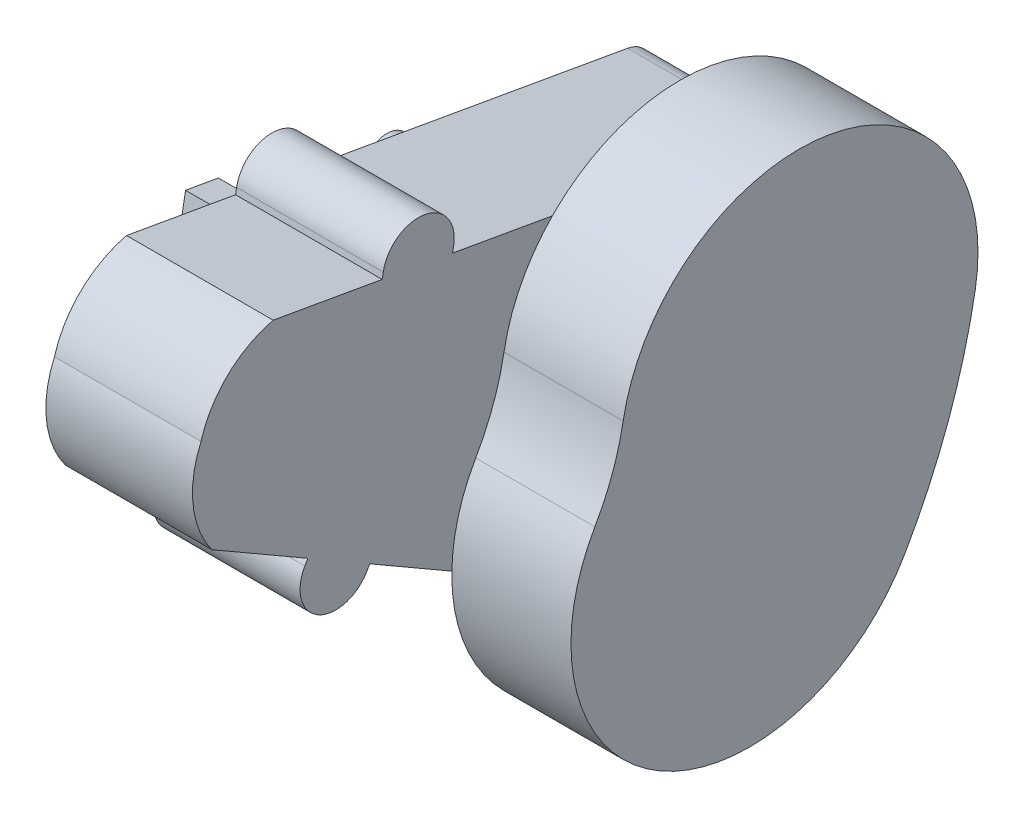
SolidWorks part; units mm, degrees
ref_plane "Front Plane" through (0, 0, 0) normal (0, 0, 1) x (1, 0, 0)
ref_plane "Top Plane" through (0, 0, 0) normal (0, 1, 0) x (1, 0, 0)
ref_plane "Right Plane" through (0, 0, 0) normal (1, 0, 0) x (0, 0, -1)
sketch "Sketch1" plane through (0, 0, 0) normal (1, 0, 0) x (0, 0, -1)
  line L0 (3.1052, 15.25) -> (16, 12.9763) construction
  line L1 (3.1052, 15.25) -> (16, 12.9763) construction
  line L2 (-0.2321, -17.5002) -> (-13.4374, -9.8761) construction
  line L3 (-0.2321, -17.5002) -> (-13.4374, -9.8761) construction
sketch "Sketch2"
sketch_block_instance "Block2-1"
sketch_block "Block2"
sketch "Sketch5" plane through (21.6, 0, 0) normal (1, 0, 0) x (0, 0, -1)
  line L1 (-0.2321, -17.5002) -> (-13.4374, -9.8761) construction
  line L2 (3.1052, 15.25) -> (16, 12.9763) construction
  line B0 (7.625, 13.2069) -> (-7.625, -13.2069)
  line B1 (8.4666, -22.4974) -> (7.9666, -23.3634)
  line B2 (18.3589, -29.3634) -> (18.8589, -28.4974)
  line B3 (18.8589, -28.4974) -> (66.3162, -55.8969)
  line B4 (73.1464, -54.0668) -> (83.3964, -36.3132)
  line B5 (81.5662, -29.4831) -> (34.1089, -2.0836)
  line B6 (34.1089, -2.0836) -> (34.6089, -1.2176)
  line B7 (24.2166, 4.7824) -> (23.7166, 3.9164)
  line B8 (23.7166, 3.9164) -> (7.625, 13.2069)
  line B9 (-7.625, -13.2069) -> (8.4666, -22.4974)
  circle B10 centre (60.6218, -35) radius 1.25
  arc B11 (7.9666, -23.3634) -> (18.3589, -29.3634) centre (13.1628, -26.3634) ccw
  arc B12 (66.3162, -55.8969) -> (73.1464, -54.0668) centre (68.8162, -51.5668) ccw
  arc B13 (83.3964, -36.3132) -> (81.5662, -29.4831) centre (79.0662, -33.8132) ccw
  arc B14 (34.6089, -1.2176) -> (24.2166, 4.7824) centre (29.4128, 1.7824) ccw
  arc B15 (7.625, 13.2069) -> (-7.625, -13.2069) centre (5.7401, -3.3141) ccw
  line B16 (2.6481, 15.0183) -> (-2.6481, -15.0183)
  line B17 (15.6506, -18.2449) -> (15.4769, -19.2297)
  line B18 (27.4683, -20.3287) -> (81.4348, -29.8444)
  line B19 (87.227, -25.7886) -> (90.7868, -5.6)
  line B20 (86.731, 0.1922) -> (32.7645, 9.708)
  line B21 (32.7645, 9.708) -> (32.9382, 10.6928)
  line B22 (21.1205, 12.7766) -> (20.9468, 11.7918)
  line B23 (20.9468, 11.7918) -> (2.6481, 15.0183)
  line B24 (-2.6481, -15.0183) -> (15.6506, -18.2449)
  circle B25 centre (68.9365, -12.1554) radius 1.25
  arc B26 (15.4769, -19.2297) -> (27.2946, -21.3135) centre (21.3858, -20.2716) ccw
  arc B27 (81.4348, -29.8444) -> (87.227, -25.7886) centre (82.303, -24.9204) ccw
  arc B28 (90.7868, -5.6) -> (86.731, 0.1922) centre (85.8628, -4.7318) ccw
  arc B29 (32.9382, 10.6928) -> (21.1205, 12.7766) centre (27.0293, 11.7347) ccw
  arc B30 (2.6481, 15.0183) -> (-2.6481, -15.0183) centre (6.5274, -1.151) ccw
sketch_block_instance "Block2-2"
sketch_block_instance "Block2-3"
sketch "Sketch7" plane through (21.6, 0, 0) normal (1, 0, 0) x (0, 0, -1)
  line L0 (-7.625, -13.2069) -> (8.4666, -22.4974) construction
  line L1 (8.4666, -22.4974) -> (7.9666, -23.3634) construction
  line L2 (18.3589, -29.3634) -> (18.8589, -28.4974) construction
  line L3 (18.8589, -28.4974) -> (66.3162, -55.8969) construction
  line L4 (-7.625, -13.2069) -> (8.4666, -22.4974)
  line L5 (8.4666, -22.4974) -> (7.9666, -23.3634)
  line L6 (18.3589, -29.3634) -> (18.8589, -28.4974)
  line L7 (18.8589, -28.4974) -> (66.3162, -55.8969)
  line L8 (86.731, 0.1922) -> (32.7645, 9.708) construction
  line L9 (32.7645, 9.708) -> (32.9382, 10.6928) construction
  line L10 (21.1205, 12.7766) -> (20.9468, 11.7918) construction
  line L11 (20.9468, 11.7918) -> (2.6481, 15.0183) construction
  line L12 (86.731, 0.1922) -> (32.7645, 9.708)
  line L13 (32.7645, 9.708) -> (32.9382, 10.6928)
  line L14 (21.1205, 12.7766) -> (20.9468, 11.7918)
  line L15 (20.9468, 11.7918) -> (2.6481, 15.0183)
  arc A1 (72.4316, -55.0206) -> (90.8524, -4.4099) centre (0, 0) ccw
  arc A2 (7.625, 13.2069) -> (-7.625, -13.2069) centre (5.7401, -3.3141) ccw construction
  arc A3 (7.9666, -23.3634) -> (18.3589, -29.3634) centre (13.1628, -26.3634) ccw construction
  arc A4 (66.3162, -55.8969) -> (73.1464, -54.0668) centre (68.8162, -51.5668) ccw construction
  arc A5 (-9.4541, 3.441) -> (-7.625, -13.2069) centre (5.7401, -3.3141) ccw
  arc A6 (7.9666, -23.3634) -> (18.3589, -29.3634) centre (13.1628, -26.3634) ccw
  arc A7 (66.3162, -55.8969) -> (72.4316, -55.0206) centre (68.8162, -51.5668) ccw
  arc A8 (90.7868, -5.6) -> (86.731, 0.1922) centre (85.8628, -4.7318) ccw construction
  arc A9 (32.9382, 10.6928) -> (21.1205, 12.7766) centre (27.0293, 11.7347) ccw construction
  arc A10 (2.6481, 15.0183) -> (-2.6481, -15.0183) centre (6.5274, -1.151) ccw construction
  arc A11 (90.8524, -4.4099) -> (86.731, 0.1922) centre (85.8628, -4.7318) ccw
  arc A12 (32.9382, 10.6928) -> (21.1205, 12.7766) centre (27.0293, 11.7347) ccw
  arc A13 (2.6481, 15.0183) -> (-9.4541, 3.441) centre (6.5274, -1.151) ccw
extrude "Boss-Extrude2" add sketch "Sketch7" against normal up to surface (24.6 mm away)
sketch "Sketch8" plane through (-3, 0, 0) normal (-1, 0, 0) x (0, 0, 1)
  line L0 (-20.9468, 11.7918) -> (-2.6481, 15.0183) construction
  line B0 (0, 0) -> (-50.3462, 0.0076) construction
  line B1 (0, 0) -> (-47.3073, -17.2265) construction
  line B2 (0, 0) -> (-48.8268, -8.6095) construction
  line B3 (-48.8268, -8.6095) -> (-50.3462, 0.0076) construction
  circle B4 centre (-50.3462, 0.0076) radius 4
  circle B5 centre (-47.3073, -17.2265) radius 4
sketch_block_instance "Block4-1"
sketch_block "Block4"
sketch "Sketch9" plane through (-3, 0, 0) normal (-1, 0, 0) x (0, 0, 1)
  line L3 (-81.5662, -29.4831) -> (-34.1089, -2.0836) construction
  line B0 (0, 0) -> (-47.3125, -17.2123) construction
  line B1 (0, 0) -> (-38.5625, -32.3677) construction
  line B2 (0, 0) -> (-42.9375, -24.79) construction
  line B3 (-42.9375, -24.79) -> (-47.3125, -17.2123) construction
  circle B4 centre (-47.3125, -17.2123) radius 4
  circle B5 centre (-38.5625, -32.3677) radius 4
sketch_block_instance "Block4-2"
sketch "Sketch10" plane through (-3, 0, 0) normal (-1, 0, 0) x (0, 0, 1)
  arc A0 (-54.3462, 0.0082) -> (-41.6263, -34.9393) centre (0, 0) ccw
  circle A1 centre (-50.3462, 0.0076) radius 4 construction
  circle A2 centre (-38.5625, -32.3677) radius 4 construction
  arc A3 (-41.6263, -34.9393) -> (-35.4987, -29.7961) centre (-38.5625, -32.3677) ccw
  arc A4 (-46.3462, 0.007) -> (-54.3462, 0.0082) centre (-50.3462, 0.0076) ccw
  arc A5 (-35.4987, -29.7961) -> (-46.3462, 0.007) centre (0, 0) cw
  circle A6 centre (-47.3073, -17.2265) radius 4 construction
extrude "Boss-Extrude3" add sketch "Sketch10" along normal up to surface (4 mm away)
sketch "Sketch11" plane through (-3, 0, 0) normal (-1, 0, 0) x (0, 0, 1)
  line L0 (-81.5662, -29.4831) -> (-34.1089, -2.0836) construction
  line L24 (-2.6481, 15.0183) -> (-20.9468, 11.7918) construction
  line B0 (-27.205, -12.0319) -> (-30.6518, -12.6397)
  line B1 (-24.6415, -15.0526) -> (-24.8881, -13.6542)
  line B2 (-19.1266, -14.0802) -> (-24.6415, -15.0526)
  line B3 (-19.7204, -10.7122) -> (-19.1266, -14.0802)
  line B4 (-14.1589, -7.7007) -> (-18.0981, -8.3952)
  line B5 (-15.8954, 2.1474) -> (-14.1589, -7.7007)
  line B6 (-19.8346, 1.4528) -> (-15.8954, 2.1474)
  line B7 (-22.7454, 6.4432) -> (-22.1515, 3.0751)
  line B8 (-28.2603, 5.4708) -> (-22.7454, 6.4432)
  line B9 (-28.0137, 4.0723) -> (-28.2603, 5.4708)
  line B10 (-33.0829, 1.1477) -> (-29.6361, 1.7554)
  line B11 (-30.6518, -12.6397) -> (-33.0829, 1.1477)
  line B12 (-15.0488, -2.6535) -> (0, 0)
  arc B13 (-24.8881, -13.6542) -> (-27.205, -12.0319) centre (-26.8577, -14.0015) ccw
  arc B14 (-18.0981, -8.3952) -> (-19.7204, -10.7122) centre (-17.7508, -10.3649) ccw
  arc B15 (-22.1515, 3.0751) -> (-19.8346, 1.4528) centre (-20.1819, 3.4224) ccw
  arc B16 (-29.6361, 1.7554) -> (-28.0137, 4.0723) centre (-29.9834, 3.725) ccw
  line B17 (-21.4492, -20.6109) -> (-24.4803, -22.3609)
  line B18 (-18.0071, -22.5727) -> (-18.7171, -21.343)
  line B19 (-13.1574, -19.7727) -> (-18.0071, -22.5727)
  line B20 (-14.8674, -16.8109) -> (-13.1574, -19.7727)
  line B21 (-10.6712, -12.0789) -> (-14.1353, -14.0789)
  line B22 (-15.6712, -3.4186) -> (-10.6712, -12.0789)
  line B23 (-19.1353, -5.4186) -> (-15.6712, -3.4186)
  line B24 (-23.5774, -1.7248) -> (-21.8674, -4.6866)
  line B25 (-28.4271, -4.5248) -> (-23.5774, -1.7248)
  line B26 (-31.4803, -10.2366) -> (-28.4492, -8.4866)
  line B27 (-24.4803, -22.3609) -> (-31.4803, -10.2366)
  line B28 (-13.2337, -7.6405) -> (0, 0)
  arc B29 (-18.7171, -21.343) -> (-21.4492, -20.6109) centre (-20.4492, -22.343) ccw
  arc B30 (-14.1353, -14.0789) -> (-14.8674, -16.8109) centre (-13.1353, -15.8109) ccw
sketch_block_instance "Block7-1"
sketch_block "Block7"
sketch_block_instance "Block7-2"
sketch "Sketch13" plane through (-3, 0, 0) normal (-1, 0, 0) x (0, 0, 1)
  line L0 (-7.625, 13.2069) -> (7.625, -13.2069) construction
  line L1 (-10.6712, -12.0789) -> (-14.1353, -14.0789) construction
  line L2 (-14.8674, -16.8109) -> (-13.1574, -19.7727) construction
  line L3 (-13.1574, -19.7727) -> (-18.0071, -22.5727) construction
  line L4 (-18.0071, -22.5727) -> (-18.7171, -21.343) construction
  line L5 (-21.4492, -20.6109) -> (-24.4803, -22.3609) construction
  line L6 (-19.8346, 1.4528) -> (-15.8954, 2.1474) construction
  line L7 (-22.7454, 6.4432) -> (-22.1515, 3.0751) construction
  line L8 (-28.2603, 5.4708) -> (-22.7454, 6.4432) construction
  line L9 (-28.0137, 4.0723) -> (-28.2603, 5.4708) construction
  line L10 (-33.0829, 1.1477) -> (-29.6361, 1.7554) construction
  line L11 (-10.6712, -12.0789) -> (-14.1353, -14.0789)
  line L12 (-14.8674, -16.8109) -> (-13.1574, -19.7727)
  line L13 (-13.1574, -19.7727) -> (-18.0071, -22.5727)
  line L14 (-18.0071, -22.5727) -> (-18.7171, -21.343)
  line L15 (-21.4492, -20.6109) -> (-24.4803, -22.3609)
  line L16 (-19.8346, 1.4528) -> (-15.8954, 2.1474)
  line L17 (-22.7454, 6.4432) -> (-22.1515, 3.0751)
  line L18 (-28.2603, 5.4708) -> (-22.7454, 6.4432)
  line L19 (-28.0137, 4.0723) -> (-28.2603, 5.4708)
  line L20 (-33.0829, 1.1477) -> (-29.6361, 1.7554)
  line L21 (-15.8954, 2.1474) -> (-14.1589, -7.7007) construction
  arc A0 (-33.0829, 1.1477) -> (-24.4803, -22.3609) centre (0.0355, -0.0615) ccw
  arc A1 (-14.1353, -14.0789) -> (-14.8674, -16.8109) centre (-13.1353, -15.8109) ccw construction
  arc A2 (-18.7171, -21.343) -> (-21.4492, -20.6109) centre (-20.4492, -22.343) ccw construction
  arc A3 (-22.1515, 3.0751) -> (-19.8346, 1.4528) centre (-20.1819, 3.4224) ccw construction
  arc A4 (-29.6361, 1.7554) -> (-28.0137, 4.0723) centre (-29.9834, 3.725) ccw construction
  arc A5 (-14.1353, -14.0789) -> (-14.8674, -16.8109) centre (-13.1353, -15.8109) ccw
  arc A6 (-18.7171, -21.343) -> (-21.4492, -20.6109) centre (-20.4492, -22.343) ccw
  arc A7 (-22.1515, 3.0751) -> (-19.8346, 1.4528) centre (-20.1819, 3.4224) ccw
  arc A8 (-29.6361, 1.7554) -> (-28.0137, 4.0723) centre (-29.9834, 3.725) ccw
  arc A10 (-10.6712, -12.0789) -> (-15.8954, 2.1474) centre (26.3924, 9.6039) cw
extrude "Boss-Extrude4" add sketch "Sketch13" along normal up to surface (10.2 mm away)
sketch "Sketch14" plane through (43.6, 0, 0) normal (1, 0, 0) x (0, 0, -1)
  line L0 (0, 0) -> (39.3827, -7) construction
  line L1 (20.963, 11.763) -> (2.6687, 15.0147) construction
  line L2 (0, 0) -> (34.641, -20) construction
  line L3 (81.5662, -29.4831) -> (34.1089, -2.0836) construction
  arc A0 (98.4568, -17.5) -> (39.3827, -7) centre (68.9198, -12.25) ccw
  circle A1 centre (68.9198, -12.25) radius 30 construction
  arc A2 (34.641, -20) -> (86.6025, -50) centre (60.6218, -35) ccw
  arc A3 (86.6025, -50) -> (98.4568, -17.5) centre (0, 0) ccw
  arc A4 (34.641, -20) -> (39.3827, -7) centre (0, 0) ccw
extrude "Boss-Extrude5" add sketch "Sketch14" against normal up to surface (20 mm away) separate body
